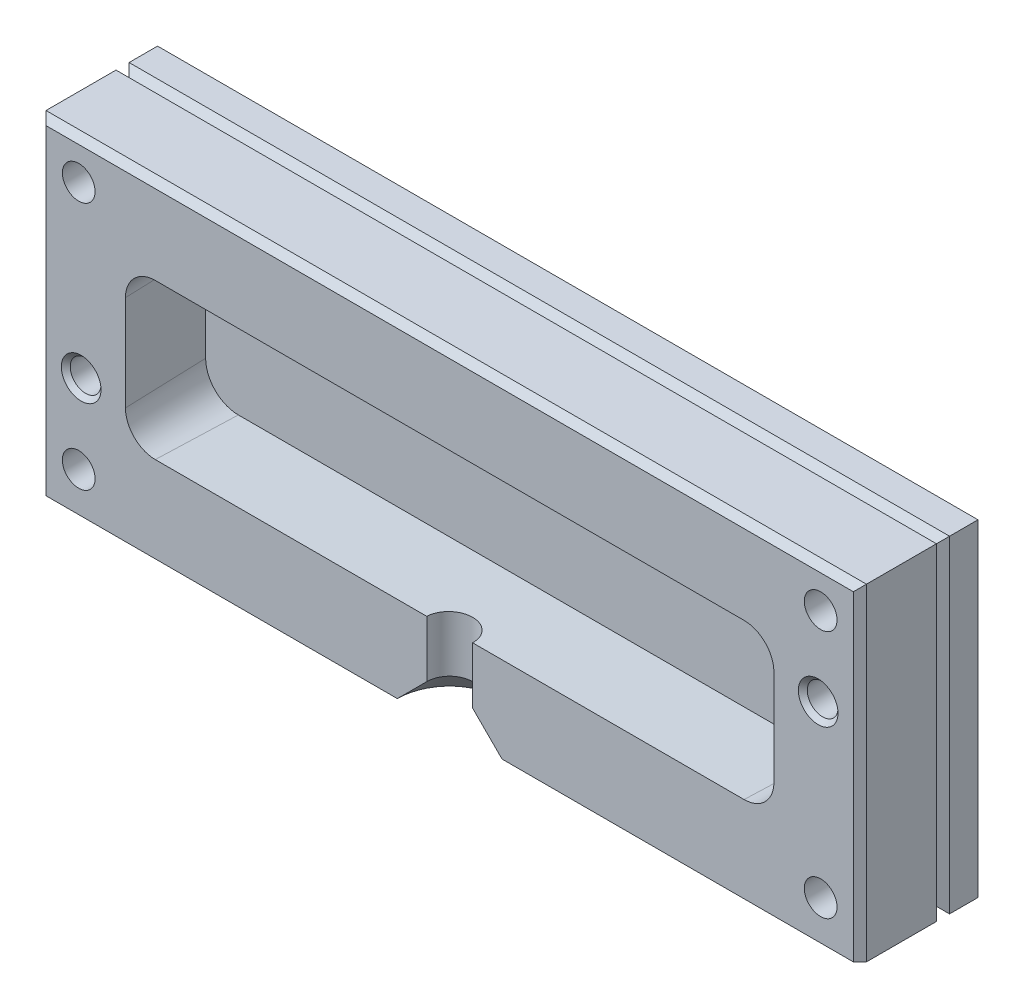
SolidWorks part; units mm, degrees
ref_plane "Front Plane" through (0, 0, 0) normal (0, 0, 1) x (1, 0, 0)
ref_plane "Top Plane" through (0, 0, 0) normal (0, 1, 0) x (1, 0, 0)
ref_plane "Right Plane" through (0, 0, 0) normal (1, 0, 0) x (0, 0, -1)
sketch "MoldSketch" plane through (0, 0, 0) normal (0, 0, 1) x (1, 0, 0)
  line L1 (-62.7, 25) -> (62.7, 25)
  line L2 (-62.7, 25) -> (-62.7, -25)
  line L3 (-62.7, -25) -> (62.7, -25)
  line L4 (62.7, 25) -> (62.7, -25)
  line L5 (-62.7, 25) -> (62.7, -25) construction
  line L6 (-62.7, -25) -> (62.7, 25) construction
  line L15 (-45, 12.3) -> (45, 12.3)
  line L16 (-50, 7.3) -> (-50, -7.3)
  line L17 (-45, -12.3) -> (45, -12.3)
  line L18 (50, 7.3) -> (50, -7.3)
  line L19 (-50, 12.3) -> (50, -12.3) construction
  line L20 (-50, -12.3) -> (50, 12.3) construction
  line L22 (0, 0) -> (0, 61.0569) construction
  line L25 (62.7, -58.9) -> (62.7, 7.3) construction
  line L26 (62.7, 7.3) -> (50, 7.3) construction
  line L27 (50, -7.3) -> (50, 7.3) construction
  arc A0 (45, 12.3) -> (50, 7.3) centre (45, 7.3) cw
  arc A1 (45, -12.3) -> (50, -7.3) centre (45, -7.3) ccw
  arc A2 (-50, -7.3) -> (-45, -12.3) centre (-45, -7.3) ccw
  arc A3 (-45, 12.3) -> (-50, 7.3) centre (-45, 7.3) ccw
  point P0 (0, 0)
  point P6 (0, 0)
  dimension "D5" = 5
  dimension "D1" = 125.4
  dimension "D2" = 50
  dimension "D3" = 12.7
  dimension "D4" = 12.7
  dimension "D12" = 100
extrude "MoldExtrusion12.7mm" add sketch "MoldSketch" along normal blind 12.7
sketch "CoverSketch" plane through (0, 0, 0) normal (0, 0, -1) x (-1, 0, 0)
  line L1 (-62.7, 25) -> (62.7, 25)
  line L2 (-62.7, 25) -> (-62.7, -25)
  line L3 (-62.7, -25) -> (62.7, -25)
  line L4 (62.7, 25) -> (62.7, -25)
extrude "CoverThickness" add sketch "CoverSketch" along normal blind 6.35 separate body
draft "Mold2DegDraft" type of draft neutral plane draft angle 2 faces to draft 8 face at (48.0178, -10.3178, 6.35) face at (50, 0, 6.35) face at (48.0178, 10.3178, 6.35) face at (0, 12.3, 6.35) face at (-48.0178, 10.3178, 6.35) face at (-50, 0, 6.35) face at (-48.0178, -10.3178, 6.35) face at (0, -12.3, 6.35) neutral plane through (0, 0, 0) neutral plane normal (0, 0, -1) parameters "D1"=2
sketch "DowelHolesLocations" plane through (0, 0, 12.7) normal (0, 0, 1) x (1, 0, 0)
  line L0 (62.7, 25) -> (-62.7, 25) construction
  line L1 (-62.7, 25) -> (-62.7, -25) construction
  line L2 (-62.7, -25) -> (62.7, -25) construction
  line L3 (62.7, -25) -> (62.7, 25) construction
  point P0 (-56.325, -6.75)
  point P5 (56.325, 6.75)
  dimension "D1" = 31.75
  dimension "D2" = 6.375
  dimension "D3" = 31.75
  dimension "D4" = 6.375
hole_wizard "Ø6.0mm Dowel Holes" positions "Sketch6" profile "Sketch7" hole size "Ø6.0" standard "ANSI Metric"
sketch "Sketch6" plane through (0, 0, 12.7) normal (0, 0, 1) x (1, 0, 0)
  point P0 (-56.325, -6.75)
  point P3 (56.325, 6.75)
sketch "Sketch7" plane through (-56.325, -6.75, 12.7) normal (1, 0, 0) x (0, -1, 0)
  line L0 (0, 0) -> (0, 9.412)
  line L1 (0, 9.412) -> (2.35, 8)
  line L2 (2.35, 8) -> (2.35, 0.68)
  line L3 (2.35, 0.68) -> (3.03, 0)
  line L5 (3.03, 0) -> (0, 0)
  line L6 (-2.35, 0.68) -> (-3.03, 0) construction
  line L10 (0, 9.412) -> (-2.35, 8) construction
  line L11 (0, -6.35) -> (0, 107.95) construction
  dimension "Hole Dia." = 4.7
  dimension "Hole Depth" = 8
  dimension "Near C'Sink Dia." = 6.06
  dimension "Near C'Sink Angle" = 90
  dimension "Drill Angle" = 118
hole_wizard "CSK for M6 Flat Head Machine Screw1" positions "InjecitonHoleLocation" profile "InjectionHole" countersink size "M6" standard "ANSI Metric"
sketch "InjecitonHoleLocation" plane through (0, -25, 0) normal (0, -1, 0) x (-1, 0, 0)
  line L1 (62.7, -12.7) -> (-62.7, -12.7) construction
  point P0 (0, -12.7)
sketch "InjectionHole" plane through (0, -25, 12.7) normal (1, 0, 0) x (0, 0, -1)
  line L0 (0, 0) -> (0, 13.1435)
  line L1 (0, 13.1435) -> (3.5, 13.1435)
  line L2 (3.5, 13.1435) -> (3.5, 4.5)
  line L3 (3.5, 4.5) -> (8, 0)
  line L5 (8, 0) -> (0, 0)
  line L6 (-3.5, 4.5) -> (-8, 0) construction
  line L10 (0, 13.1435) -> (-3.5, 13.1435) construction
  line L11 (0, -6.35) -> (0, 107.95) construction
  dimension "Hole Dia." = 7
  dimension "Hole Depth" = 13.1435
  dimension "Near C'Sink Dia." = 16
  dimension "Near C'Sink Angle" = 90
  dimension "Drill Angle" = 180
sketch "ThreadHolesLocations" plane through (0, 0, 0) normal (0, 0, -1) x (-1, 0, 0)
  line L0 (-62.7, -25) -> (-62.7, 25) construction
  line L1 (-62.7, 25) -> (62.7, 25) construction
  line L2 (0, 0) -> (0, -44.31) construction
  line L3 (0, 0) -> (82.7787, 0) construction
  point P0 (-56.7, 19)
  point P5 (-56.7, 19)
  point P14 (56.7, 19)
  point P16 (56.7, -19)
  point P17 (-56.7, -19)
  dimension "D1" = 6
  dimension "D2" = 6
chamfer "Chamfer1" distance 1 angle 45 7 edges at (0, 25, 12.7) (-62.7, 0, 12.7) (62.7, 0, 12.7) (62.7, 0, 0) (0, 25, 0) (-62.7, 0, 0) (0, -25, 0)
sketch "CoverHolesLocations" plane through (0, 0, -6.35) normal (0, 0, -1) x (-1, 0, 0)
  line L0 (-37.9403, 19.2073) -> (-37.9403, -25.1027) construction
  line L1 (-37.9403, 19.2073) -> (44.8384, 19.2073) construction
  point P0 (-94.6403, 38.2073)
  point P1 (-94.6403, 38.2073)
  point P6 (18.7597, 38.2073)
  point P7 (18.7597, 0.2073)
  point P8 (-94.6403, 0.2073)
hole_wizard "Tap Drill for M6x1.0 Tap1" positions "Sketch8" profile "Sketch9" hole size "M6x1.0" standard "ANSI Metric" end condition through all
sketch "Sketch8" plane through (-40.3988, -67.586, 0) normal (0, 0, -1) x (-1, 0, 0)
  point P0 (-97.0988, 86.586)
  point P3 (16.3012, 86.586)
  point P6 (16.3012, 48.586)
  point P9 (-97.0988, 48.586)
sketch "Sketch9" plane through (56.7, 19, 0) normal (1, 0, 0) x (0, 1, 0)
  line L0 (0, 0) -> (0, 12.7)
  line L1 (0, 12.7) -> (2.5, 12.7)
  line L2 (2.5, 12.7) -> (2.5, 0)
  line L5 (2.5, 0) -> (0, 0)
  line L11 (0, -6.35) -> (0, 107.95) construction
  dimension "Thru Hole Dia." = 5
  dimension "Thru Hole Depth" = 12.7
chamfer "CoverChamfer" distance 1 angle 45 8 edges at (62.7, 0, 0) (0, -25, 0) (-62.7, 0, 0) (0, 25, 0) (-62.7, 0, -6.35) (0, -25, -6.35) (62.7, 0, -6.35) (0, 25, -6.35)
hole_wizard "Tap Drill for M6x1.0 Tap2" positions "Sketch10" profile "Sketch11" hole size "M6x1.0" standard "ANSI Metric" end condition through all
sketch "Sketch10" plane through (-40.3988, -67.586, 0) normal (0, 0, 1) x (1, 0, 0)
  point P0 (-16.3012, 86.586)
  point P3 (97.0988, 86.586)
  point P6 (97.0988, 48.586)
  point P9 (-16.3012, 48.586)
sketch "Sketch11" plane through (-56.7, 19, 0) normal (1, 0, 0) x (0, -1, 0)
  line L0 (0, 0) -> (0, 6.35)
  line L1 (0, 6.35) -> (2.5, 6.35)
  line L2 (2.5, 6.35) -> (2.5, 0)
  line L3 (2.5, 0) -> (0, 0)
  line L4 (0, -6.35) -> (0, 107.95) construction
  dimension "Thru Hole Dia." = 5
  dimension "Thru Hole Depth" = 6.35
